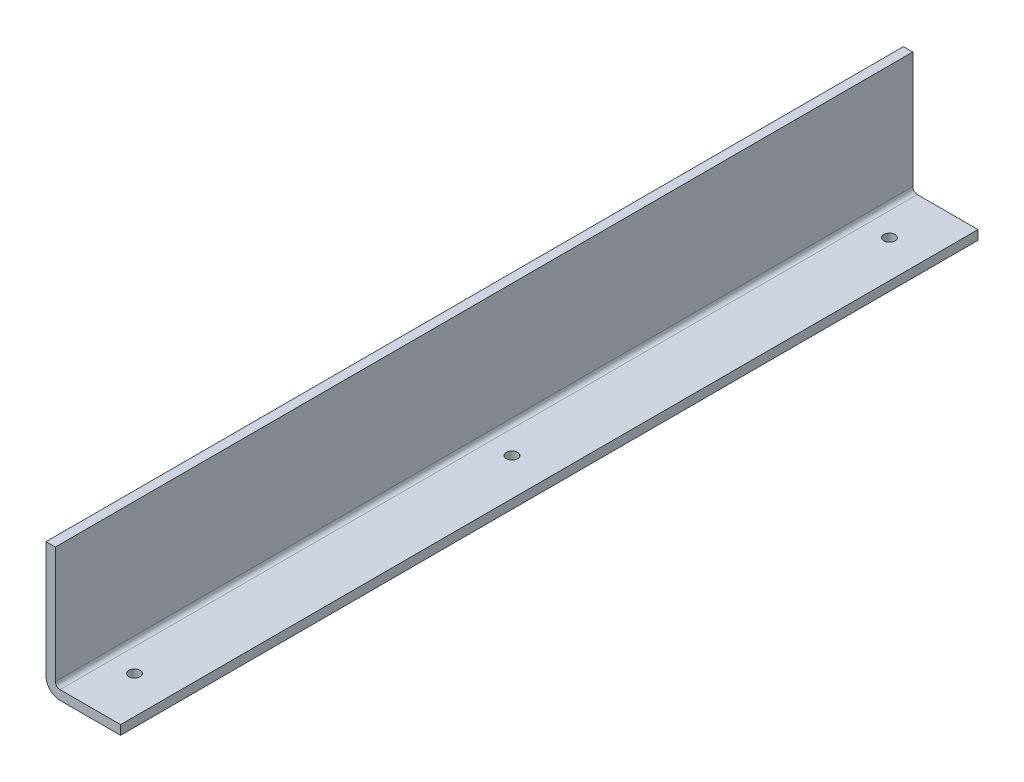
SolidWorks part; units mm, degrees
material "3.0205 (EN-AW 1200)"
ref_plane "前视基准面" through (0, 0, 0) normal (0, 0, 1) x (1, 0, 0)
ref_plane "上视基准面" through (0, 0, 0) normal (0, 1, 0) x (1, 0, 0)
ref_plane "右视基准面" through (0, 0, 0) normal (1, 0, 0) x (0, 0, -1)
sketch "草图1" plane through (0, 0, 0) normal (0, 0, 1) x (1, 0, 0)
  line L0 (0, 140) -> (0, 15)
  line L1 (15, 0) -> (80, 0)
  line L2 (10, 140) -> (10, 15)
  line L3 (15, 10) -> (80, 10)
  line L4 (0, 140) -> (10, 140)
  line L5 (80, 10) -> (80, 0)
  arc A0 (0, 15) -> (15, 0) centre (15, 15) ccw
  arc A1 (10, 15) -> (15, 10) centre (15, 15) ccw
  point P6 (0, 0)
  dimension "D3" = 15
  dimension "D1" = 140
  dimension "D2" = 80
  dimension "D4" = 10
extrude "凸台-拉伸1" add sketch "草图1" along normal mid plane 920
sketch "草图2" plane through (0, 0, 0) normal (0, 0, 1) x (1, 0, 0)
  line L0 (40, 38.7283) -> (40, -17.0396) construction
  line L1 (40, 10) -> (46, 10)
  line L2 (80, 10) -> (15, 10) construction
  line L3 (46, 10) -> (46, 0)
  line L4 (15, 0) -> (80, 0) construction
  line L5 (46, 0) -> (40, 0)
  line L6 (0, 140) -> (0, 15) construction
  line L7 (40, 10) -> (40, 0)
  dimension "D1" = 6
  dimension "D2" = 40
revolve "切除-旋转1" cut sketch "草图2" angle 360 about L0
pattern_linear "阵列(线性)1" count 2 spacing 405 along (0, 0, 1) count 2 spacing 405 along (0, 0, -1) of "切除-旋转1"
